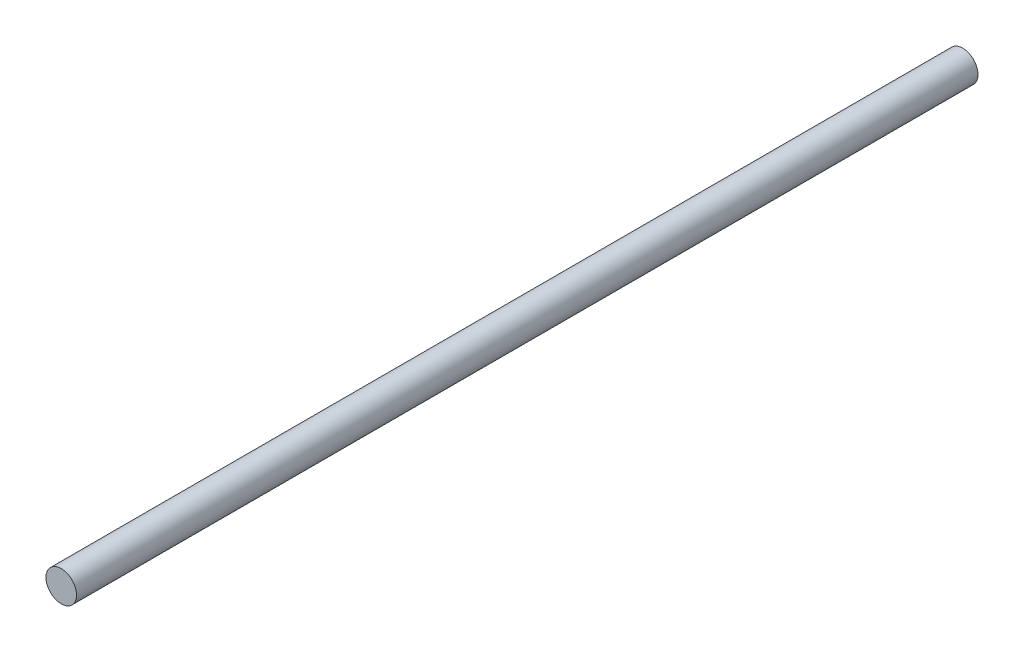
SolidWorks part; units mm, degrees
ref_plane "Plano frontal" through (0, 0, 0) normal (0, 0, 1) x (1, 0, 0)
ref_plane "Plano superior" through (0, 0, 0) normal (0, 1, 0) x (1, 0, 0)
ref_plane "Plano direito" through (0, 0, 0) normal (1, 0, 0) x (0, 0, -1)
sketch "Esboço1" plane through (0, 0, 0) normal (0, 0, 1) x (1, 0, 0)
  circle A0 centre (0, 0) radius 5
  dimension "D1" = 10
extrude "Ressalto-extrusão1" add sketch "Esboço1" along normal mid plane 295
